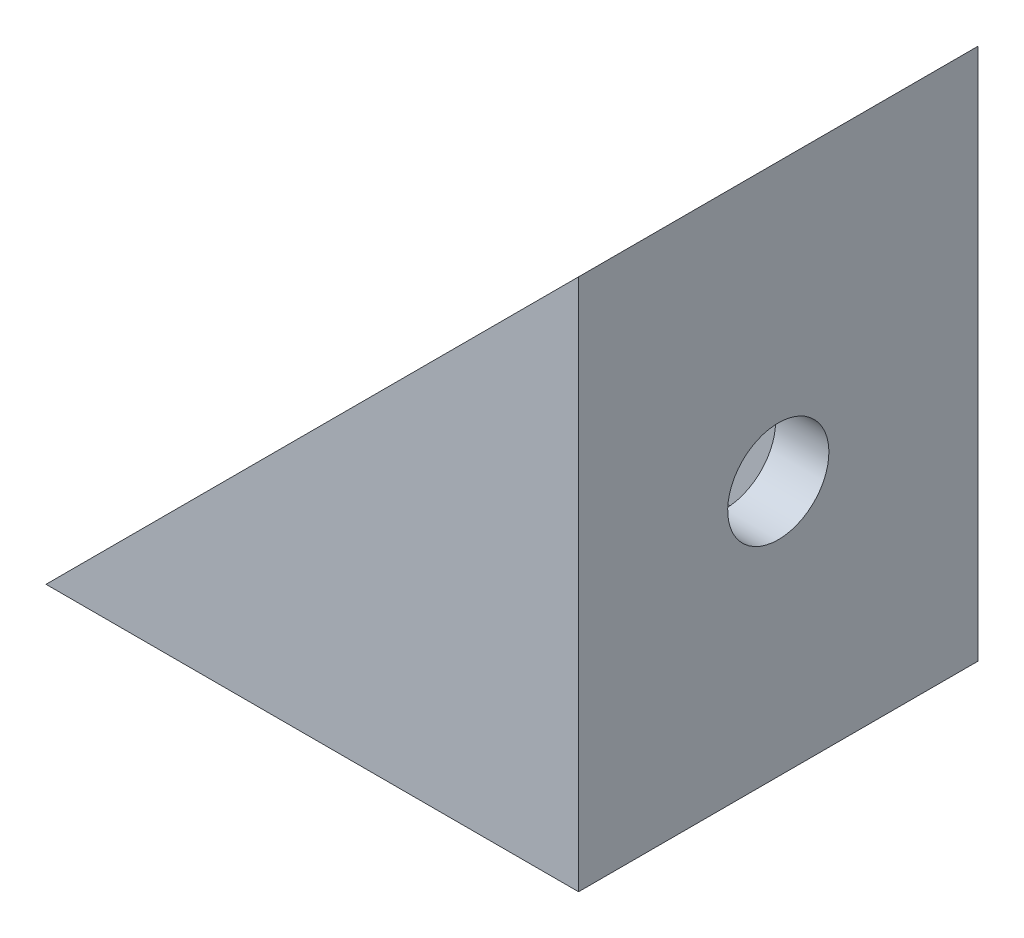
SolidWorks part; units mm, degrees
material "PLA"
ref_plane "Front" through (0, 0, 0) normal (0, 0, 1) x (1, 0, 0)
ref_plane "Top" through (0, 0, 0) normal (0, 1, 0) x (1, 0, 0)
ref_plane "Right" through (0, 0, 0) normal (1, 0, 0) x (0, 0, -1)
sketch "Sketch1" plane through (0, 0, 0) normal (0, 0, 1) x (1, 0, 0)
  line L0 (0, 0) -> (-20, 0)
  line L1 (-20, 0) -> (0, 20)
  line L2 (0, 20) -> (0, 0)
  dimension "D1" = 20
extrude "Boss-Extrude1" add sketch "Sketch1" along normal blind 15
sketch "Sketch2" plane through (0, 0, 15) normal (0, 0, 1) x (1, 0, 0)
  line L0 (-18, 2) -> (-2, 18)
  line L1 (0, 20) -> (-20, 0) construction
  line L2 (-2, 18) -> (-2, 2)
  line L3 (-2, 2) -> (-18, 2)
  line L4 (-20, 0) -> (0, 0) construction
  line L5 (0, 0) -> (0, 20) construction
  dimension "D1" = 2
  dimension "D2" = 2
extrude "Cut-Extrude1" cut sketch "Sketch2" against normal blind 11.8 from offset 1.6 offset against normal yes
sketch "Sketch3" plane through (-2, 0, 0) normal (-1, 0, 0) x (0, 0, 1)
  line L0 (15, 20) -> (0, 20) construction
  line L1 (15, 0) -> (0, 0) construction
  circle A0 centre (7.5, 9.6) radius 1.9
  point P5 (7.5, 20)
  dimension "D1" = 3.8
  dimension "D2" = 9.6
extrude "Cut-Extrude2" cut sketch "Sketch3" against normal through all
sketch "Sketch4" plane through (0, 2, 0) normal (0, 1, 0) x (1, 0, 0)
  line L0 (-20, -15) -> (-20, 0) construction
  line L1 (0, -15) -> (0, 0) construction
  circle A0 centre (-9.6, -7.5) radius 1.9
  point P5 (-20, -7.5)
  dimension "D1" = 3.8
  dimension "D2" = 9.6
extrude "Cut-Extrude3" cut sketch "Sketch4" against normal through all
